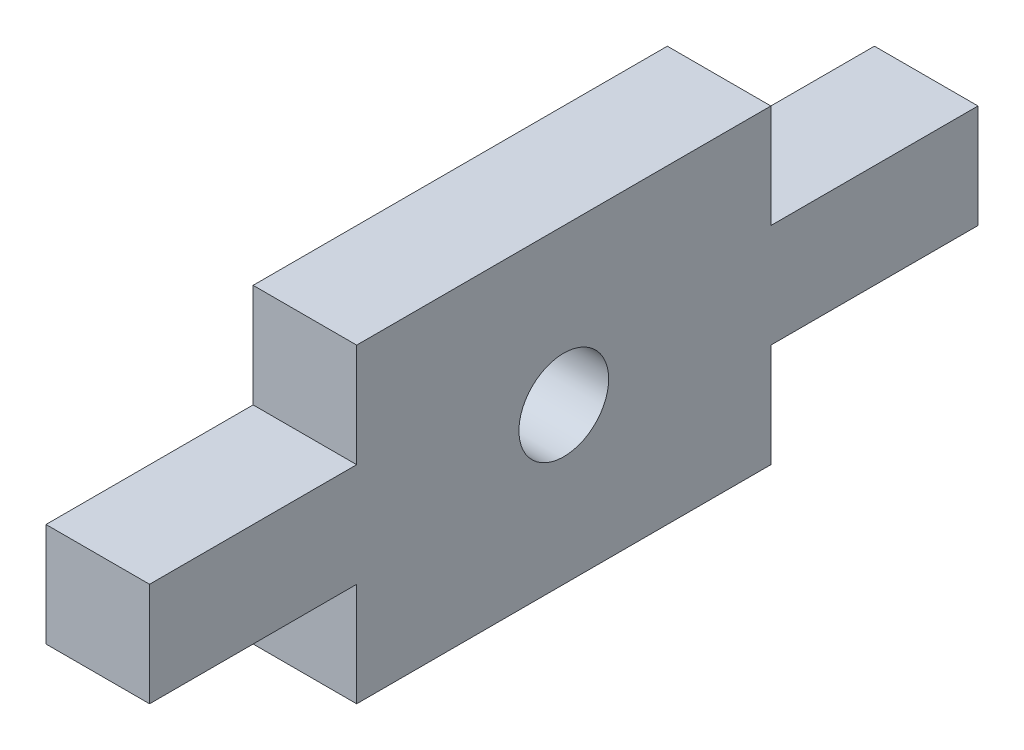
SolidWorks part; units mm, degrees
material "Acrílico (médio-alto impacto)"
ref_plane "Plano frontal" through (0, 0, 0) normal (0, 0, 1) x (1, 0, 0)
ref_plane "Plano superior" through (0, 0, 0) normal (0, 1, 0) x (1, 0, 0)
ref_plane "Plano direito" through (0, 0, 0) normal (1, 0, 0) x (0, 0, -1)
sketch "Principal" plane through (0, 0, 0) normal (1, 0, 0) x (0, 0, -1)
  line L1 (-12, -1.5) -> (12, -1.5)
  line L2 (-12, -1.5) -> (-12, 1.5)
  line L3 (-12, 1.5) -> (12, 1.5)
  line L4 (12, -1.5) -> (12, 1.5)
  line L5 (0, 1.5) -> (0, -1.5) construction
  line L6 (-12, 0) -> (12, 0) construction
  line L7 (-6, 4.5) -> (6, 4.5)
  line L8 (-6, 4.5) -> (-6, 1.5)
  line L9 (-6, 1.5) -> (6, 1.5)
  line L10 (6, 4.5) -> (6, 1.5)
  line L11 (0, 1.5) -> (0, 4.5) construction
  line L12 (-6, 3) -> (6, 3) construction
  line L13 (-6, -4.5) -> (6, -4.5)
  line L14 (-6, -4.5) -> (-6, -1.5)
  line L15 (-6, -1.5) -> (6, -1.5)
  line L16 (6, -4.5) -> (6, -1.5)
  line L17 (0, -1.5) -> (0, -4.5) construction
  line L18 (-6, -3) -> (6, -3) construction
  point P0 (0, 0)
  point P4 (0, 3)
  point P8 (0, -3)
  dimension "D1" = 24
  dimension "D2" = 3
  dimension "D3" = 12
  dimension "D4" = 9
extrude "Base" add sketch "Principal" along normal blind 3 contours L10 L7 L8 L3 | L1 L4 L3 L2 | L13 L16 L1 L14
hole_wizard "Furo de diâmetro Ø2.6 (2.6)1" positions "Esboço3" profile "Esboço4" hole size "Ø2.6" standard "ISO" end condition through all
sketch "Esboço3" plane through (3, 0, 0) normal (1, 0, 0) x (0, 0, -1)
  point P0 (0, 0)
sketch "Esboço4" plane through (3, 0, 0) normal (0, 1, 0) x (0, 0, -1)
  line L0 (0, 0) -> (0, 3)
  line L1 (0, 3) -> (1.3, 3)
  line L2 (1.3, 3) -> (1.3, 0)
  line L5 (1.3, 0) -> (0, 0)
  line L11 (0, -6.35) -> (0, 107.95) construction
  dimension "Thru Hole Dia." = 2.6
  dimension "Thru Hole Depth" = 3
